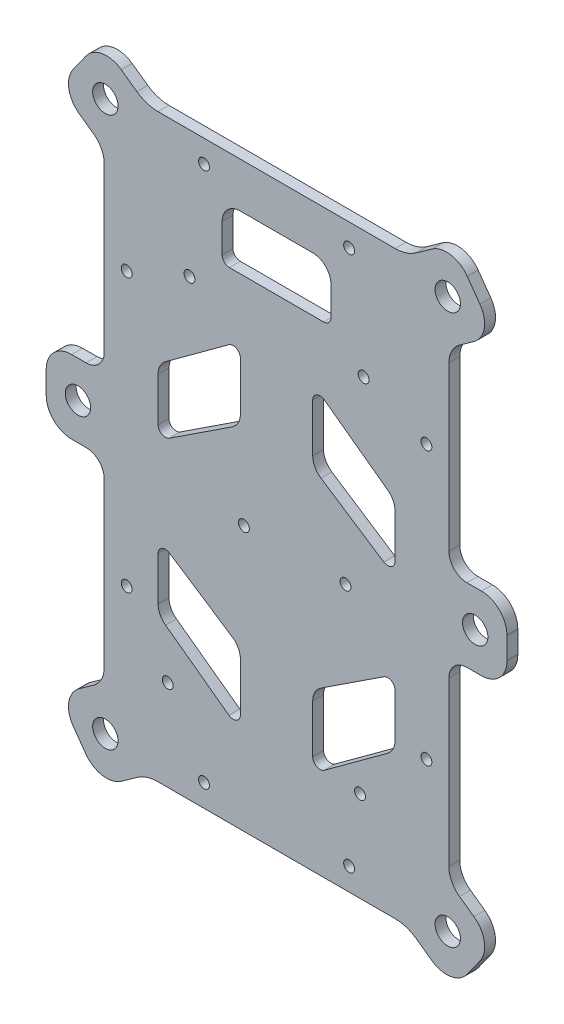
SolidWorks part; units mm, degrees
ref_plane "Front Plane" through (0, 0, 0) normal (0, 0, 1) x (1, 0, 0)
ref_plane "Top Plane" through (0, 0, 0) normal (0, 1, 0) x (1, 0, 0)
ref_plane "Right Plane" through (0, 0, 0) normal (1, 0, 0) x (0, 0, -1)
sketch "Sketch1" plane through (0, 0, 0) normal (0, 0, 1) x (1, 0, 0)
  line L1 (-24.4982, 18.6863) -> (-28.8129, 21.7633)
  line L2 (-42.0602, 15.2434) -> (-38.5765, 20.1284)
  line L3 (-36.4405, 2.638) -> (-40.4254, 5.4798)
  line L4 (-33.5049, -3.0612) -> (-33.5049, -48.0612)
  line L5 (-42.5049, -53.0612) -> (-38.5049, -53.0612)
  line L6 (46.6543, -45.8778) -> (46.6543, -57.9168)
  line L7 (-49.5003, -60.2356) -> (-49.5003, -66.1084)
  line L8 (-49.5049, -60.0612) -> (-49.5003, -60.2356)
  line L9 (46.6871, 16.828) -> (-18.692, 16.828)
  line L10 (77.5, -60.0612) -> (77.4954, -60.2356)
  line L11 (77.4954, -60.2356) -> (77.4954, -66.1084)
  line L12 (70.5, -53.0612) -> (66.5, -53.0612)
  line L13 (61.5, -3.0612) -> (61.5, -48.0612)
  line L14 (64.4356, 2.638) -> (68.4204, 5.4798)
  line L15 (70.0553, 15.2434) -> (66.5716, 20.1284)
  line L16 (52.4933, 18.6863) -> (56.808, 21.7633)
  line L17 (26.2216, -98.3525) -> (43.5571, -86.9768)
  line L18 (52.4933, -145.0303) -> (56.808, -148.1073)
  line L19 (70.0553, -141.5874) -> (66.5716, -146.4724)
  line L20 (64.4356, -128.9821) -> (68.4204, -131.8238)
  line L21 (61.5, -123.2828) -> (61.5, -78.2828)
  line L22 (70.5, -73.2828) -> (66.5, -73.2828)
  line L23 (77.5, -66.2828) -> (77.4954, -66.1084)
  line L24 (46.6871, -143.172) -> (-18.692, -143.172)
  line L25 (-49.5049, -66.2828) -> (-49.5003, -66.1084)
  line L26 (-42.5049, -73.2828) -> (-38.5049, -73.2828)
  line L27 (-33.5049, -123.2828) -> (-33.5049, -78.2828)
  line L28 (-36.4405, -128.9821) -> (-40.4254, -131.8238)
  line L29 (-42.0602, -141.5874) -> (-38.5765, -146.4724)
  line L30 (-24.4982, -145.0303) -> (-28.8129, -148.1073)
  line L31 (27.1462, -117.5047) -> (44.6077, -104.7224)
  line L32 (23.9648, -109.8335) -> (23.9648, -115.8908)
  line L33 (23.9648, -109.8335) -> (23.9648, -102.5328)
  line L34 (46.6543, -100.6879) -> (46.6543, -88.6489)
  line L35 (-18.6593, -100.6879) -> (-18.6593, -88.6489)
  line L36 (4.0303, -109.8335) -> (4.0303, -102.5328)
  line L37 (4.0303, -109.8335) -> (4.0303, -115.8908)
  line L38 (0.8489, -117.5047) -> (-16.6126, -104.7224)
  line L39 (1.7734, -98.3525) -> (-15.562, -86.9768)
  line L40 (23.9648, -36.7322) -> (23.9648, -44.0329)
  line L41 (23.9648, -36.7322) -> (23.9648, -30.6748)
  line L42 (27.1462, -29.061) -> (44.6077, -41.8432)
  line L43 (26.2216, -48.2132) -> (43.5571, -59.5889)
  line L44 (1.7734, -48.2132) -> (-15.562, -59.5889)
  line L45 (0.8489, -29.061) -> (-16.6126, -41.8432)
  line L46 (4.0303, -36.7322) -> (4.0303, -30.6748)
  line L47 (4.0303, -36.7322) -> (4.0303, -44.0329)
  line L48 (-18.6593, -45.8778) -> (-18.6593, -57.9168)
  line L51 (0.9975, -10.5612) -> (26.9975, -10.5612)
  line L52 (28.9975, -8.5612) -> (28.9975, -0.5612)
  line L53 (23.9975, 4.4388) -> (3.9975, 4.4388)
  line L54 (-1.0025, -0.5612) -> (-1.0025, -8.5612)
  circle A0 centre (68.7454, -63.172) radius 3.5
  circle A1 centre (-40.7503, -63.172) radius 3.5
  circle A2 centre (33.9975, 10.6334) radius 1.5
  arc A3 (-38.5049, -53.0612) -> (-33.5049, -48.0612) centre (-38.5049, -48.0612) ccw
  arc A4 (-49.5049, -60.0612) -> (-42.5049, -53.0612) centre (-42.5049, -60.0612) cw
  circle A5 centre (-6.0025, 10.6334) radius 1.5
  circle A6 centre (-33.1943, 12.6054) radius 3.5
  arc A7 (-24.4982, 18.6863) -> (-18.692, 16.828) centre (-18.692, 26.828) ccw
  arc A8 (-40.4254, 5.4798) -> (-42.0602, 15.2434) centre (-36.361, 11.179) cw
  arc A9 (-38.5765, 20.1284) -> (-28.8129, 21.7633) centre (-32.8773, 16.0641) cw
  arc A10 (-33.5049, -3.0612) -> (-36.4405, 2.638) centre (-40.5049, -3.0612) ccw
  arc A11 (61.5, -3.0612) -> (64.4356, 2.638) centre (68.5, -3.0612) cw
  arc A12 (66.5716, 20.1284) -> (56.808, 21.7633) centre (60.8724, 16.0641) ccw
  arc A13 (68.4204, 5.4798) -> (70.0553, 15.2434) centre (64.3561, 11.179) ccw
  arc A14 (52.4933, 18.6863) -> (46.6871, 16.828) centre (46.6871, 26.828) cw
  circle A15 centre (61.1894, 12.6054) radius 3.5
  circle A16 centre (-6.0025, -136.9774) radius 1.5
  arc A17 (77.5, -60.0612) -> (70.5, -53.0612) centre (70.5, -60.0612) ccw
  arc A18 (66.5, -53.0612) -> (61.5, -48.0612) centre (66.5, -48.0612) cw
  circle A19 centre (33.9975, -136.9774) radius 1.5
  circle A20 centre (-27.3149, -100.7828) radius 1.5
  circle A21 centre (55.31, -100.7828) radius 1.5
  circle A22 centre (-27.3149, -25.5612) radius 1.5
  circle A23 centre (55.31, -25.5612) radius 1.5
  circle A24 centre (-16.0025, -118.172) radius 1.5
  arc A25 (66.5, -73.2828) -> (61.5, -78.2828) centre (66.5, -78.2828) ccw
  arc A26 (77.5, -66.2828) -> (70.5, -73.2828) centre (70.5, -66.2828) cw
  circle A27 centre (36.9975, -118.172) radius 1.5
  circle A28 centre (61.1894, -138.9495) radius 3.5
  arc A29 (52.4933, -145.0303) -> (46.6871, -143.172) centre (46.6871, -153.172) ccw
  arc A30 (68.4204, -131.8238) -> (70.0553, -141.5874) centre (64.3561, -137.523) cw
  arc A31 (66.5716, -146.4724) -> (56.808, -148.1073) centre (60.8724, -142.4081) cw
  arc A32 (61.5, -123.2828) -> (64.4356, -128.9821) centre (68.5, -123.2828) ccw
  arc A33 (-33.5049, -123.2828) -> (-36.4405, -128.9821) centre (-40.5049, -123.2828) cw
  arc A34 (-38.5765, -146.4724) -> (-28.8129, -148.1073) centre (-32.8773, -142.4081) ccw
  arc A35 (-40.4254, -131.8238) -> (-42.0602, -141.5874) centre (-36.361, -137.523) ccw
  arc A36 (-24.4982, -145.0303) -> (-18.692, -143.172) centre (-18.692, -153.172) cw
  circle A37 centre (-33.1943, -138.9495) radius 3.5
  arc A39 (-49.5049, -66.2828) -> (-42.5049, -73.2828) centre (-42.5049, -66.2828) ccw
  arc A40 (-38.5049, -73.2828) -> (-33.5049, -78.2828) centre (-38.5049, -78.2828) cw
  circle A50 centre (37.9975, -18.172) radius 1.5
  circle A51 centre (-10.0025, -18.172) radius 1.5
  circle A52 centre (32.9975, -70.172) radius 1.5
  circle A53 centre (5.0025, -70.172) radius 1.5
  arc A54 (46.6543, -100.6879) -> (44.6077, -104.7224) centre (41.6543, -100.6879) cw
  arc A55 (43.5571, -86.9768) -> (46.6543, -88.6489) centre (44.6543, -88.6489) cw
  arc A56 (23.9648, -115.8908) -> (27.1462, -117.5047) centre (25.9648, -115.8908) ccw
  arc A57 (26.2216, -98.3525) -> (23.9648, -102.5328) centre (28.9648, -102.5328) ccw
  arc A58 (1.7734, -98.3525) -> (4.0303, -102.5328) centre (-0.9697, -102.5328) cw
  arc A59 (4.0303, -115.8908) -> (0.8489, -117.5047) centre (2.0303, -115.8908) cw
  arc A60 (-15.562, -86.9768) -> (-18.6593, -88.6489) centre (-16.6593, -88.6489) ccw
  arc A61 (-18.6593, -100.6879) -> (-16.6126, -104.7224) centre (-13.6593, -100.6879) ccw
  arc A62 (26.2216, -48.2132) -> (23.9648, -44.0329) centre (28.9648, -44.0329) cw
  arc A63 (23.9648, -30.6748) -> (27.1462, -29.061) centre (25.9648, -30.6748) cw
  arc A64 (43.5571, -59.5889) -> (46.6543, -57.9168) centre (44.6543, -57.9168) ccw
  arc A65 (46.6543, -45.8778) -> (44.6077, -41.8432) centre (41.6543, -45.8778) ccw
  arc A66 (-18.6593, -45.8778) -> (-16.6126, -41.8432) centre (-13.6593, -45.8778) cw
  arc A67 (-15.562, -59.5889) -> (-18.6593, -57.9168) centre (-16.6593, -57.9168) cw
  arc A68 (4.0303, -30.6748) -> (0.8489, -29.061) centre (2.0303, -30.6748) ccw
  arc A69 (1.7734, -48.2132) -> (4.0303, -44.0329) centre (-0.9697, -44.0329) ccw
  arc A70 (3.9975, 4.4388) -> (-1.0025, -0.5612) centre (3.9975, -0.5612) ccw
  arc A71 (23.9975, 4.4388) -> (28.9975, -0.5612) centre (23.9975, -0.5612) cw
  arc A72 (28.9975, -8.5612) -> (26.9975, -10.5612) centre (26.9975, -8.5612) cw
  arc A73 (0.9975, -10.5612) -> (-1.0025, -8.5612) centre (0.9975, -8.5612) cw
  point P25 (-34.5122, 25.8276)
  point P29 (-34.5122, 25.8276)
  point P64 (62.5072, 25.8276)
  point P95 (62.5072, -152.1716)
  point P124 (-34.5122, -152.1716)
  dimension "D6" = 5
  dimension "D7" = 2
  dimension "D10" = 5
  dimension "D11" = 2
  dimension "D1" = 10
  dimension "D2" = 7
  dimension "D3" = 7
  dimension "D4" = 5
  dimension "D5" = 7
  dimension "D8" = 2
  dimension "D9" = 5
extrude "Бобышка-Вытянуть1" add sketch "Sketch1" against normal blind 3
